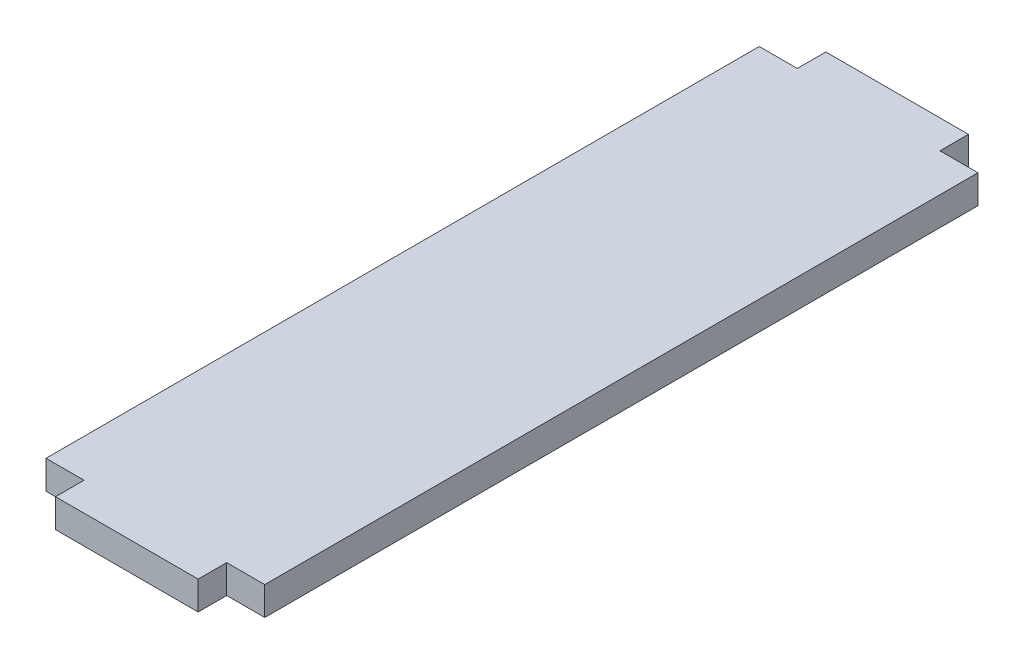
SolidWorks part; units mm, degrees
material "AISI 304"
ref_plane "Front Plane" through (0, 0, 0) normal (0, 0, 1) x (1, 0, 0)
ref_plane "Top Plane" through (0, 0, 0) normal (0, 1, 0) x (1, 0, 0)
ref_plane "Right Plane" through (0, 0, 0) normal (1, 0, 0) x (0, 0, -1)
sketch "Sketch1" plane through (0, 0, 0) normal (0, 1, 0) x (1, 0, 0)
  line L0 (3.75, 18.75) -> (5.75, 18.75)
  line L1 (-5.75, -18.75) -> (-3.75, -18.75)
  line L2 (-5.75, -18.75) -> (-5.75, 18.75)
  line L3 (-5.75, 18.75) -> (-3.75, 18.75)
  line L4 (5.75, -18.75) -> (5.75, 18.75)
  line L5 (-5.75, -18.75) -> (5.75, 18.75) construction
  line L6 (-5.75, 18.75) -> (5.75, -18.75) construction
  line L8 (-3.75, 18.75) -> (-3.75, 20.25)
  line L9 (-3.75, 20.25) -> (3.75, 20.25)
  line L10 (3.75, 18.75) -> (3.75, 20.25)
  line L12 (-3.75, -18.75) -> (-3.75, -20.25)
  line L13 (-3.75, -20.25) -> (3.75, -20.25)
  line L14 (3.75, -18.75) -> (3.75, -20.25)
  line L15 (3.75, -18.75) -> (5.75, -18.75)
  point P0 (0, 0)
  dimension "D1" = 2
  dimension "D2" = 2
  dimension "D3" = 7.5
  dimension "D4" = 2
  dimension "D5" = 2
  dimension "D6" = 1.5
  dimension "D7" = 1.5
  dimension "D8" = 37.5
extrude "Boss-Extrude1" add sketch "Sketch1" along normal blind 1.5
